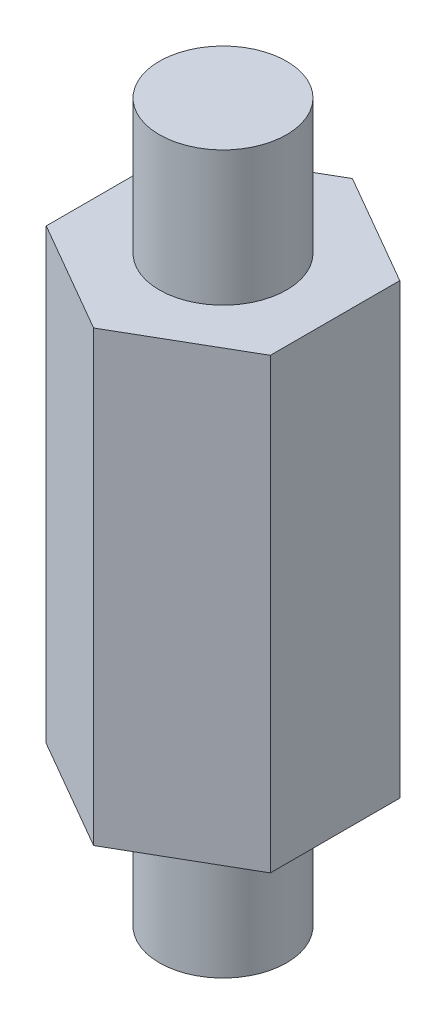
SolidWorks part; units mm, degrees
ref_plane "Front Plane" through (0, 0, 0) normal (0, 0, 1) x (1, 0, 0)
ref_plane "Top Plane" through (0, 0, 0) normal (0, 1, 0) x (1, 0, 0)
ref_plane "Right Plane" through (0, 0, 0) normal (1, 0, 0) x (0, 0, -1)
sketch "Sketch1" plane through (0, 0, 0) normal (0, 1, 0) x (1, 0, 0)
  line L1 (0, 2.8868) -> (-2.5, 1.4434)
  line L2 (-2.5, 1.4434) -> (-2.5, -1.4434)
  line L3 (-2.5, -1.4434) -> (0, -2.8868)
  line L4 (0, -2.8868) -> (2.5, -1.4434)
  line L5 (2.5, -1.4434) -> (2.5, 1.4434)
  line L6 (2.5, 1.4434) -> (0, 2.8868)
  circle A0 centre (0, 0) radius 2.5 construction
  dimension "D1" = 5
extrude "Boss-Extrude1" add sketch "Sketch1" along normal blind 10
sketch "Sketch2" plane through (0, 10, 0) normal (0, 1, 0) x (1, 0, 0)
  circle A0 centre (0, 0) radius 1.42
  dimension "D1" = 2.84
extrude "Boss-Extrude2" add sketch "Sketch2" along normal blind 3
sketch "Sketch3" plane through (0, 0, 0) normal (0, -1, 0) x (-1, 0, 0)
  circle A0 centre (0, 0) radius 1.42
  dimension "D1" = 2.84
extrude "Boss-Extrude3" add sketch "Sketch3" along normal blind 3
